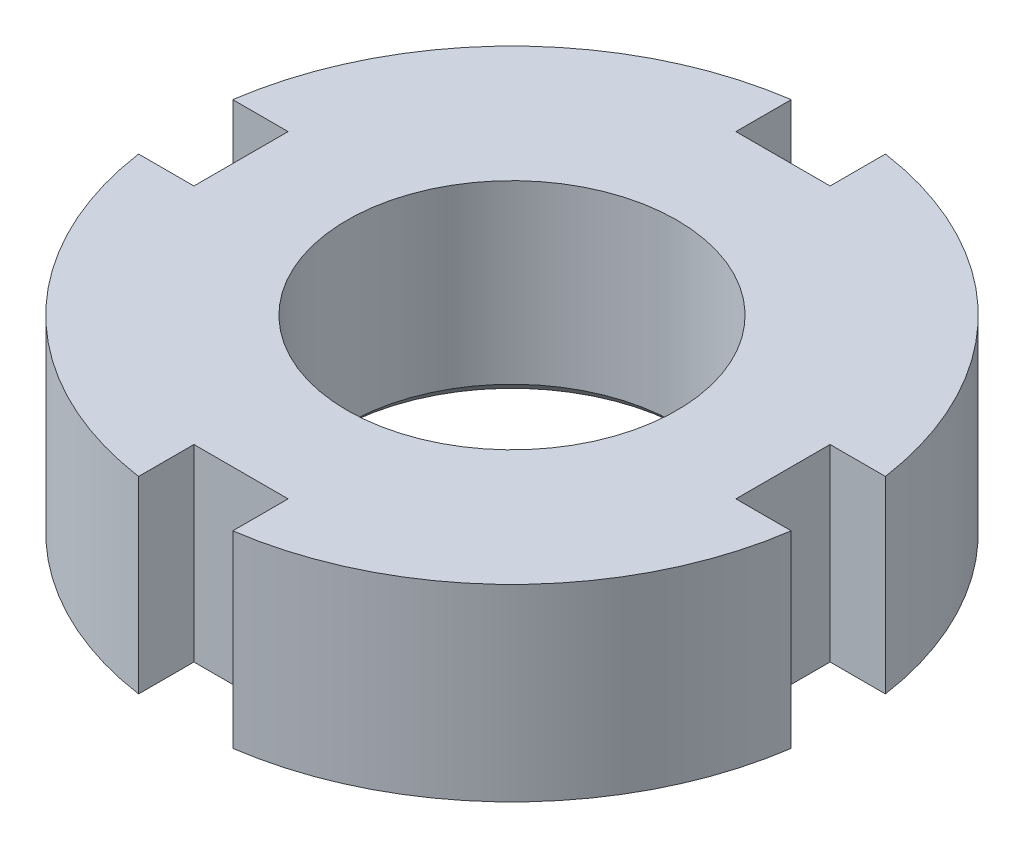
SolidWorks part; units mm, degrees
ref_plane "Front Plane" through (0, 0, 0) normal (0, 0, 1) x (1, 0, 0)
ref_plane "Top Plane" through (0, 0, 0) normal (0, 1, 0) x (1, 0, 0)
ref_plane "Right Plane" through (0, 0, 0) normal (1, 0, 0) x (0, 0, -1)
sketch "Sketch1" plane through (0, 0, 0) normal (0, 1, 0) x (1, 0, 0)
  line L0 (0, 0) -> (34.0881, 0) construction
  line L1 (4, -23.0128) -> (4, -27.7128)
  line L2 (23.0128, 4) -> (27.7128, 4)
  line L3 (23.0128, 4) -> (23.0128, -4)
  line L4 (23.0128, -4) -> (27.7128, -4)
  line L5 (4, -23.0128) -> (-4, -23.0128)
  line L6 (-4, -23.0128) -> (-4, -27.7128)
  line L7 (-23.0128, -4) -> (-27.7128, -4)
  line L8 (-23.0128, -4) -> (-23.0128, 4)
  line L9 (-23.0128, 4) -> (-27.7128, 4)
  line L10 (-4, 23.0128) -> (-4, 27.7128)
  line L11 (-4, 23.0128) -> (4, 23.0128)
  line L12 (4, 23.0128) -> (4, 27.7128)
  arc A0 (-4, 27.7128) -> (-27.7128, 4) centre (0, 0) ccw
  arc A1 (-27.7128, -4) -> (-4, -27.7128) centre (0, 0) ccw
  arc A2 (4, -27.7128) -> (27.7128, -4) centre (0, 0) ccw
  arc A3 (27.7128, 4) -> (4, 27.7128) centre (0, 0) ccw
  point P5 (0, 0)
  point P23 (0, 0)
  dimension "D1" = 56
  dimension "D2" = 4.7
  dimension "D3" = 8
  dimension "D4" = 4
extrude "Boss-Extrude1" add sketch "Sketch1" along normal mid plane 16
hole_wizard "M30x2.0 Tapped Hole5" positions "Sketch4" profile "Sketch5" tap size "M30x2.0" standard "ANSI Metric"
sketch "Sketch4" plane through (0, -8, 0) normal (0, -1, 0) x (-1, 0, 0)
  point P0 (0, 0)
sketch "Sketch5" plane through (0, -8, 0) normal (1, 0, 0) x (0, 0, -1)
  line L0 (0, 0) -> (0, 24.412)
  line L1 (0, 24.412) -> (14, 16)
  line L2 (14, 16) -> (14, 1.025)
  line L3 (14, 1.025) -> (15.025, 0)
  line L5 (15.025, 0) -> (0, 0)
  line L6 (-14, 1.025) -> (-15.025, 0) construction
  line L10 (0, 24.412) -> (-14, 16) construction
  line L11 (0, -6.35) -> (0, 107.95) construction
  dimension "Tap Drill Dia." = 28
  dimension "Tap Drill Depth" = 16
  dimension "Near C'Sink Dia." = 30.05
  dimension "Near C'Sink Angle" = 90
  dimension "Drill Angle" = 118
cosmetic thread "Hole Thread1" parameters "D1"=10, "D2"=30
